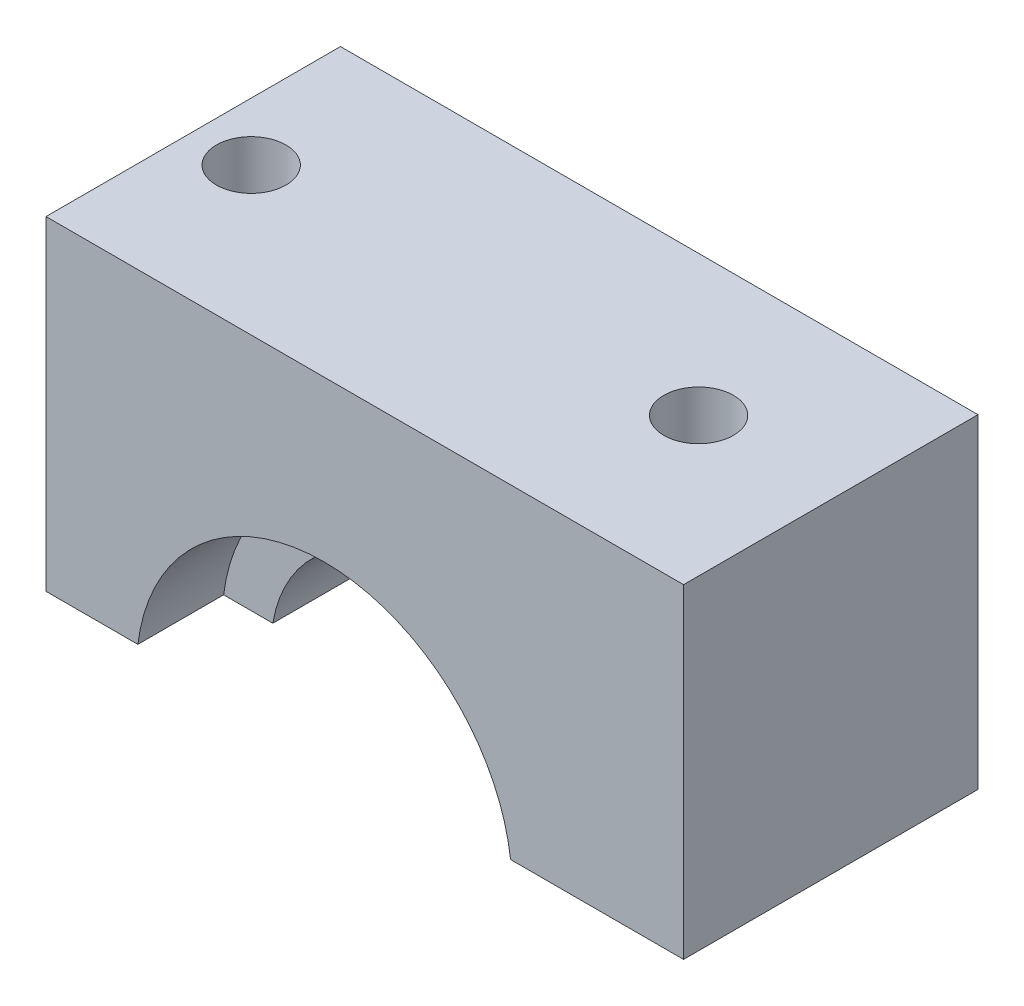
SolidWorks part; units mm, degrees
ref_plane "Front Plane" through (0, 0, 0) normal (0, 0, 1) x (1, 0, 0)
ref_plane "Top Plane" through (0, 0, 0) normal (0, 1, 0) x (1, 0, 0)
ref_plane "Right Plane" through (0, 0, 0) normal (1, 0, 0) x (0, 0, -1)
sketch "Sketch1" plane through (0, 0, 0) normal (0, 1, 0) x (1, 0, 0)
  line L1 (0, 0) -> (-24, 0)
  line L2 (0, 0) -> (0, 12.7)
  line L3 (0, 12.7) -> (-24, 12.7)
  line L4 (-24, 0) -> (-24, 12.7)
  dimension "D1" = 12.7
  dimension "D2" = 24
extrude "Boss-Extrude1" add sketch "Sketch1" along normal blind 15
sketch "Sketch2" plane through (0, 0, 0) normal (0, 0, 1) x (1, 0, 0)
  line L0 (-12, 15) -> (-12, 0) construction
  line L1 (-24, 15) -> (0, 15) construction
  line L2 (-24, 0) -> (0, 0) construction
  circle A0 centre (-12, 0) radius 6
  dimension "D1" = 12
extrude "Cut-Extrude1" cut sketch "Sketch2" against normal blind 15
sketch "Sketch3" plane through (0, 0, 0) normal (0, 0, 1) x (1, 0, 0)
  line L0 (-12, 15) -> (-12, 0) construction
  line L1 (-24, 15) -> (0, 15) construction
  line L2 (-12, 0) -> (-6, 0) construction
  circle A0 centre (-12, 0) radius 8.1
  dimension "D1" = 16.2
extrude "Cut-Extrude2" cut sketch "Sketch3" against normal blind 3.7
sketch "Sketch5" plane through (0, 0, -12.7) normal (0, 0, -1) x (-1, 0, 0)
  circle A0 centre (12, 0) radius 8.1 construction
  circle A1 centre (12, 0) radius 8.1
extrude "Cut-Extrude3" cut sketch "Sketch5" against normal blind 3.4
sketch "Sketch6" plane through (0, 0, 0) normal (0, -1, 0) x (1, 0, 0)
  line L0 (-20.1, -12.7) -> (-24, -12.7) construction
  line L1 (-24, -12.7) -> (0, -12.7)
  line L2 (-24, -12.7) -> (-24, 0)
  line L3 (-24, 0) -> (0, 0)
  line L4 (0, -12.7) -> (0, 0)
  line L5 (-24, -12.7) -> (-24, 0) construction
  dimension "D1" = 24
  dimension "D2" = 12.7
extrude "Cut-Extrude4" cut sketch "Sketch6" against normal blind 1
sketch "Sketch7" plane through (0, 1, 0) normal (0, -1, 0) x (1, 0, 0)
  line L0 (-24, 0) -> (-24, -12.7) construction
  line L1 (-20.038, 0) -> (-24, 0) construction
  line L2 (0, -12.7) -> (0, 0) construction
  line L4 (0, 0) -> (-12, 0) construction
  line L5 (-3.962, -12.7) -> (0, -12.7) construction
  circle A0 centre (-21.5, -6.35) radius 1.5
  circle A2 centre (-2.5, -6.65) radius 1.5
  dimension "D1" = 3
  dimension "D3" = 6.35
  dimension "D6" = 13.3
  dimension "D7" = 2.5
  dimension "D2" = 2.5
  dimension "D4" = 12
  dimension "D5" = 12.7
extrude "Cut-Extrude5" cut sketch "Sketch7" against normal blind 22
sketch "Sketch8" plane through (0, 0, 0) normal (1, 0, 0) x (0, 0, -1)
  line L4 (0, 15) -> (0, 1)
  line L5 (0, 1) -> (12.7, 1)
  line L6 (12.7, 1) -> (12.7, 15)
  line L7 (12.7, 15) -> (0, 15)
  line L8 (0, 15) -> (0, 1)
  line L9 (0, 1) -> (12.7, 1)
  line L10 (12.7, 1) -> (12.7, 15)
  line L11 (12.7, 15) -> (0, 15)
  dimension "D1" = 0
extrude "Boss-Extrude2" add sketch "Sketch8" along normal blind 3.5
